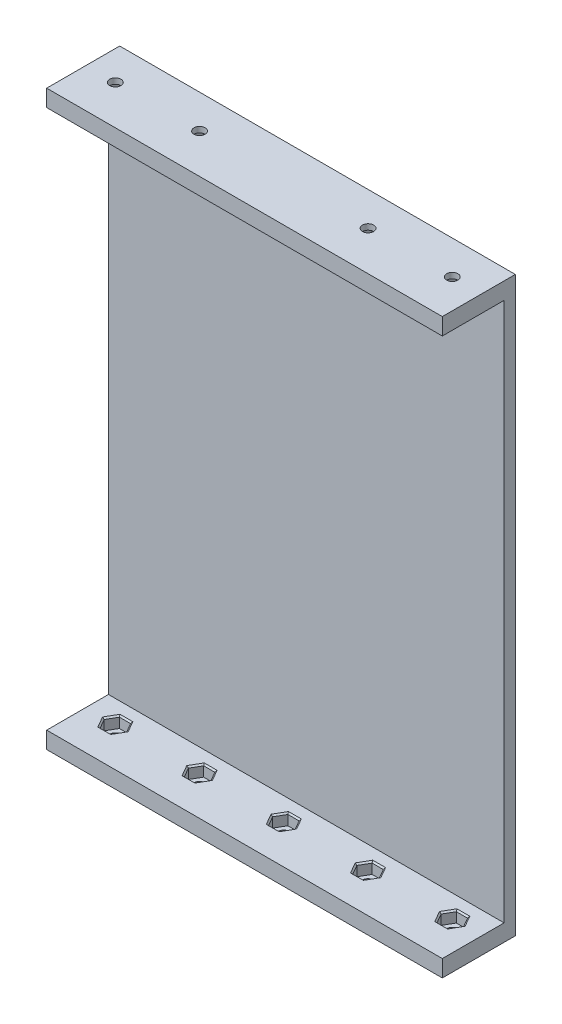
SolidWorks part; units mm, degrees
ref_plane "Front Plane" through (0, 0, 0) normal (0, 0, 1) x (1, 0, 0)
ref_plane "Top Plane" through (0, 0, 0) normal (0, 1, 0) x (1, 0, 0)
ref_plane "Right Plane" through (0, 0, 0) normal (1, 0, 0) x (0, 0, -1)
sketch "Sketch1" plane through (0, 0, 0) normal (0, 0, 1) x (1, 0, 0)
  line L1 (-70.45, -102) -> (70.45, -102)
  line L2 (-70.45, -102) -> (-70.45, 102)
  line L3 (-70.45, 102) -> (70.45, 102)
  line L4 (70.45, -102) -> (70.45, 102)
  line L5 (-70.45, -102) -> (70.45, 102) construction
  line L6 (-70.45, 102) -> (70.45, -102) construction
  point P0 (0, 0)
  dimension "D1" = 140.9
  dimension "D2" = 204
extrude "Boss-Extrude1" add sketch "Sketch1" against normal blind 4
sketch "Sketch4" plane through (0, 0, 0) normal (0, 0, 1) x (1, 0, 0)
  line L0 (70.45, -102) -> (70.45, 102) construction
  line L1 (-70.45, 102) -> (70.45, 102)
  line L2 (-70.45, 102) -> (-70.45, 96)
  line L3 (-70.45, 96) -> (70.45, 96)
  line L4 (70.45, 102) -> (70.45, 96)
  line L6 (-70.45, -102) -> (70.45, -102)
  line L7 (-70.45, -102) -> (-70.45, -96)
  line L8 (-70.45, -96) -> (70.45, -96)
  line L9 (70.45, -102) -> (70.45, -96)
  dimension "D1" = 6
  dimension "D2" = 6
extrude "Boss-Extrude3" add sketch "Sketch4" along normal blind 22
sketch "Sketch5" plane through (0, 102, 0) normal (0, 1, 0) x (1, 0, 0)
  line L0 (-999.5545, -8) -> (49000.4455, -8) construction
  line L1 (70.45, 4) -> (-70.45, 4) construction
  line L2 (0, -14.3) -> (0, 14.3) construction
  circle A0 centre (-30, -8) radius 2
  circle A1 centre (-60, -8) radius 2
  circle A4 centre (60, -8) radius 2
  circle A5 centre (30, -8) radius 2
  dimension "D2" = 4
  dimension "D1" = 12
  dimension "D3" = 30
  dimension "D4" = 60
extrude "Cut-Extrude1" cut sketch "Sketch5" against normal through all both and the other way through all
sketch "Sketch8" plane through (0, -96, 0) normal (0, 1, 0) x (1, 0, 0)
  line L0 (-26.0163, -8) -> (-28.0081, -4.55)
  line L1 (-56.0163, -8) -> (-58.0081, -4.55)
  line L2 (-58.0081, -4.55) -> (-61.9919, -4.55)
  line L3 (-61.9919, -4.55) -> (-63.9837, -8)
  line L4 (-63.9837, -8) -> (-61.9919, -11.45)
  line L5 (-61.9919, -11.45) -> (-58.0081, -11.45)
  line L6 (-58.0081, -11.45) -> (-56.0163, -8)
  line L7 (-28.0081, -4.55) -> (-31.9919, -4.55)
  line L8 (-31.9919, -4.55) -> (-33.9837, -8)
  line L9 (-33.9837, -8) -> (-31.9919, -11.45)
  line L10 (-31.9919, -11.45) -> (-28.0081, -11.45)
  line L11 (-28.0081, -11.45) -> (-26.0163, -8)
  line L12 (3.9837, -8) -> (1.9919, -4.55) [skipped]
  line L13 (1.9919, -4.55) -> (-1.9919, -4.55) [skipped]
  line L14 (-1.9919, -4.55) -> (-3.9837, -8) [skipped]
  line L15 (-3.9837, -8) -> (-1.9919, -11.45) [skipped]
  line L16 (-1.9919, -11.45) -> (1.9919, -11.45) [skipped]
  line L17 (1.9919, -11.45) -> (3.9837, -8) [skipped]
  line L18 (33.9837, -8) -> (31.9919, -4.55)
  line L19 (31.9919, -4.55) -> (28.0081, -4.55)
  line L20 (28.0081, -4.55) -> (26.0163, -8)
  line L21 (26.0163, -8) -> (28.0081, -11.45)
  line L22 (28.0081, -11.45) -> (31.9919, -11.45)
  line L23 (31.9919, -11.45) -> (33.9837, -8)
  line L24 (63.9837, -8) -> (61.9919, -4.55)
  line L25 (61.9919, -4.55) -> (58.0081, -4.55)
  line L26 (58.0081, -4.55) -> (56.0163, -8)
  line L27 (56.0163, -8) -> (58.0081, -11.45)
  line L28 (58.0081, -11.45) -> (61.9919, -11.45)
  line L29 (61.9919, -11.45) -> (63.9837, -8)
  line L30 (-56.0163, -8) -> (-26.0163, -8) construction
  circle A0 centre (-60, -8) radius 3.45 construction
  dimension "D1" = 6.9
  dimension "D3" = 30
  dimension "D2" = 5
extrude "Cut-Extrude4" cut sketch "Sketch8" against normal blind 4
mirror "Mirror1" about plane through (0, 0, 0) normal (0, 1, 0) of "Cut-Extrude4"
sketch "Sketch9" plane through (0, -96, 0) normal (0, 1, 0) x (1, 0, 0)
  line L0 (70.45, 4) -> (-70.45, 4) construction
  circle A0 centre (0, -8) radius 2
  dimension "D2" = 4
  dimension "D1" = 12
extrude "Cut-Extrude5" cut sketch "Sketch9" against normal through all
sketch "Sketch10" plane through (0, -96, 0) normal (0, 1, 0) x (1, 0, 0)
  line L1 (1.9919, -4.55) -> (-1.9919, -4.55)
  line L2 (-1.9919, -4.55) -> (-3.9837, -8)
  line L3 (-3.9837, -8) -> (-1.9919, -11.45)
  line L4 (-1.9919, -11.45) -> (1.9919, -11.45)
  line L5 (1.9919, -11.45) -> (3.9837, -8)
  line L6 (3.9837, -8) -> (1.9919, -4.55)
  circle A0 centre (0, -8) radius 3.45 construction
  dimension "D1" = 6.9
extrude "Cut-Extrude6" cut sketch "Sketch10" against normal up to surface (4 mm away) up to face at (-30, -100, 8)
chamfer "Chamfer1" distance 0.5 angle 45 54 edges at (60, 96, 11.45) (57.0122, 96, 9.725) (57.0122, 96, 6.275) (60, 96, 4.55) (62.9878, 96, 6.275) (62.9878, 96, 9.725) (30, 96, 11.45) (27.0122, 96, 9.725) (27.0122, 96, 6.275) (30, 96, 4.55) (32.9878, 96, 6.275) (32.9878, 96, 9.725) (-30, 96, 11.45) (-32.9878, 96, 9.725) (-32.9878, 96, 6.275) (-30, 96, 4.55) (-27.0122, 96, 6.275) (-27.0122, 96, 9.725) (-60, 96, 11.45) (-62.9878, 96, 9.725) (-62.9878, 96, 6.275) (-60, 96, 4.55) (-57.0122, 96, 6.275) (-57.0122, 96, 9.725) (60, -96, 4.55) (57.0122, -96, 6.275) (57.0122, -96, 9.725) (60, -96, 11.45) (62.9878, -96, 9.725) (62.9878, -96, 6.275) (30, -96, 4.55) (27.0122, -96, 6.275) (27.0122, -96, 9.725) (30, -96, 11.45) (32.9878, -96, 9.725) (32.9878, -96, 6.275) (-2.9878, -96, 6.275) (-2.9878, -96, 9.725) (0, -96, 11.45) (2.9878, -96, 9.725) (2.9878, -96, 6.275) (0, -96, 4.55) (-30, -96, 4.55) (-32.9878, -96, 6.275) (-32.9878, -96, 9.725) (-30, -96, 11.45) (-27.0122, -96, 9.725) (-27.0122, -96, 6.275) (-60, -96, 4.55) (-62.9878, -96, 6.275) (-62.9878, -96, 9.725) (-60, -96, 11.45) (-57.0122, -96, 9.725) (-57.0122, -96, 6.275)
